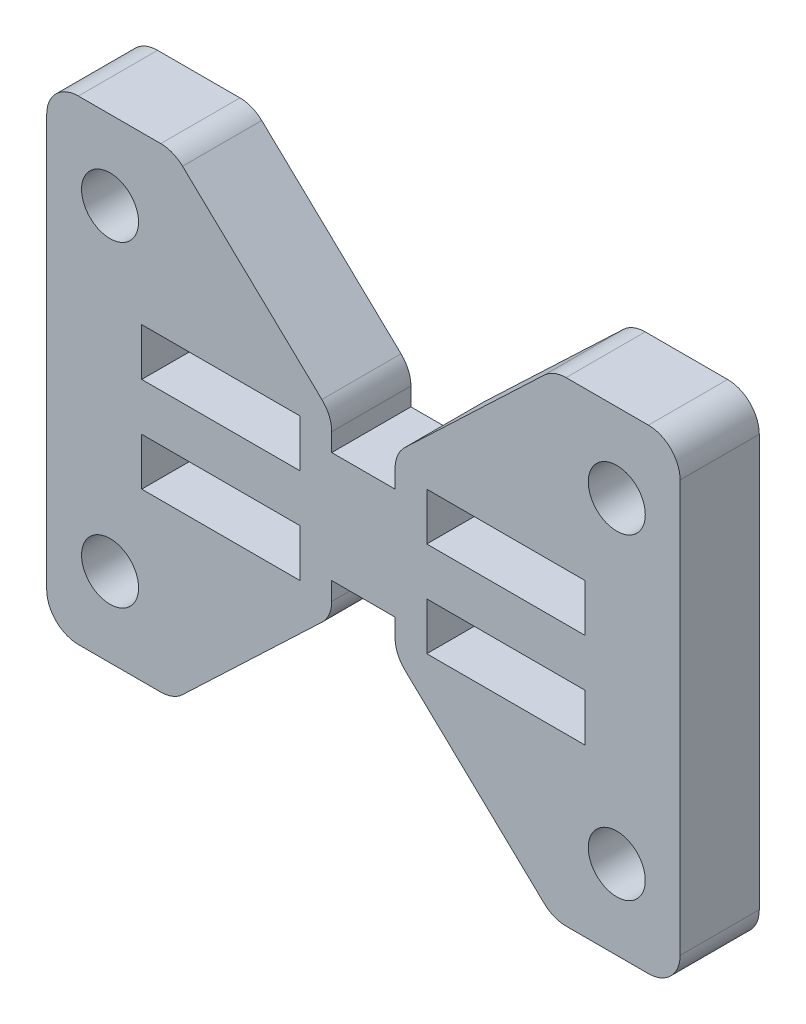
SolidWorks part; units mm, degrees
ref_plane "Front Plane" through (0, 0, 0) normal (0, 0, 1) x (1, 0, 0)
ref_plane "Top Plane" through (0, 0, 0) normal (0, 1, 0) x (1, 0, 0)
ref_plane "Right Plane" through (0, 0, 0) normal (1, 0, 0) x (0, 0, -1)
sketch "Sketch1" plane through (0, 0, 0) normal (0, 0, 1) x (1, 0, 0)
  line L1 (-2.54, -4.445) -> (2.54, -4.445)
  line L2 (-2.54, 4.445) -> (2.54, 4.445)
  line L7 (0, 4.445) -> (0, -4.445) construction
  line L13 (-2.54, -4.445) -> (-2.54, -6.985)
  line L15 (-15.24, 19.05) -> (-25.4, 19.05)
  line L16 (-2.54, 6.985) -> (-2.54, 4.445)
  line L17 (-15.24, -19.05) -> (-25.4, -19.05)
  line L18 (-25.4, 19.05) -> (-25.4, -19.05)
  line L19 (-17.78, 1.905) -> (-5.08, 1.905)
  line L20 (-17.78, 1.905) -> (-17.78, 5.715)
  line L21 (-17.78, 5.715) -> (-5.08, 5.715)
  line L22 (-5.08, 1.905) -> (-5.08, 5.715)
  line L26 (-2.54, -6.985) -> (-15.24, -19.05)
  line L27 (-2.54, 6.985) -> (-15.24, 19.05)
  line L28 (-25.4, 0) -> (0, 0) construction
  line L29 (-5.08, -1.905) -> (-5.08, -5.715)
  line L30 (-17.78, -5.715) -> (-5.08, -5.715)
  line L31 (-17.78, -1.905) -> (-5.08, -1.905)
  line L32 (-17.78, -1.905) -> (-17.78, -5.715)
  line L33 (17.78, -1.905) -> (17.78, -5.715)
  line L34 (17.78, -1.905) -> (5.08, -1.905)
  line L35 (17.78, -5.715) -> (5.08, -5.715)
  line L36 (5.08, -1.905) -> (5.08, -5.715)
  line L37 (2.54, 6.985) -> (15.24, 19.05)
  line L38 (2.54, -6.985) -> (15.24, -19.05)
  line L39 (5.08, 1.905) -> (5.08, 5.715)
  line L40 (17.78, 5.715) -> (5.08, 5.715)
  line L41 (17.78, 1.905) -> (17.78, 5.715)
  line L42 (17.78, 1.905) -> (5.08, 1.905)
  line L43 (25.4, 19.05) -> (25.4, -19.05)
  line L44 (15.24, -19.05) -> (25.4, -19.05)
  line L45 (2.54, 6.985) -> (2.54, 4.445)
  line L46 (15.24, 19.05) -> (25.4, 19.05)
  line L47 (2.54, -4.445) -> (2.54, -6.985)
  circle A6 centre (-20.32, -12.7) radius 2.286
  circle A8 centre (-20.32, 12.7) radius 2.286
  circle A9 centre (20.32, 12.7) radius 2.286
  circle A10 centre (20.32, -12.7) radius 2.286
  point P0 (0, 0)
  point P39 (-20.32, -19.05)
  point P41 (-25.4, 0)
  point P55 (25.4, 0)
  point P56 (20.32, -19.05)
  dimension "D3" = 50.8
  dimension "D9" = 38.1
  dimension "D10" = 4.572
  dimension "D2" = 1.905
  dimension "D4" = 12.7
  dimension "D7" = 8.89
  dimension "D11" = 5.08
  dimension "D12" = 3.81
  dimension "D13" = 12.7
  dimension "D14" = 7.62
  dimension "D15" = 2.54
  dimension "D16" = 10.16
  dimension "D17" = 22.86
extrude "Boss-Extrude1" add sketch "Sketch1" along normal mid plane 6.35
fillet "Fillet1" radius 2.54 12 edges at (2.54, 6.985, 0) (15.24, 19.05, 0) (25.4, 19.05, 0) (25.4, -19.05, 0) (15.24, -19.05, 0) (2.54, -6.985, 0) (-25.4, -19.05, 0) (-15.24, -19.05, 0) (-2.54, -6.985, 0) (-2.54, 6.985, 0) (-15.24, 19.05, 0) (-25.4, 19.05, 0)
sketch "Sketch4" plane through (0, 0, 0) normal (0, 1, 0) x (1, 0, 0)
  line L1 (-17.78, -3.175) -> (-5.08, -3.175) construction
  line L2 (-11.43, -4.445) -> (-11.43, 3.175) construction
  line L3 (5.08, 3.175) -> (17.78, 3.175) construction
  line L4 (-5.08, 3.175) -> (-17.78, 3.175) construction
  circle A0 centre (-11.43, -4.445) radius 5.08
  dimension "D3" = 10.16
  dimension "D2" = 1.27
extrude "Cut-Extrude1" [suppressed] cut sketch "Sketch4" against normal mid plane 16.51
sketch "Sketch5" plane through (0, 0, 0) normal (0, 1, 0) x (1, 0, 0)
  line L0 (11.43, -4.445) -> (11.43, 3.175) construction
  line L3 (5.08, 3.175) -> (17.78, 3.175) construction
  line L4 (5.08, 3.175) -> (17.78, 3.175) construction
  circle A0 centre (11.43, -4.445) radius 5.08
  dimension "D1" = 10.16
  dimension "D2" = 7.62
extrude "Cut-Extrude2" [suppressed] cut sketch "Sketch5" against normal mid plane 16.51
